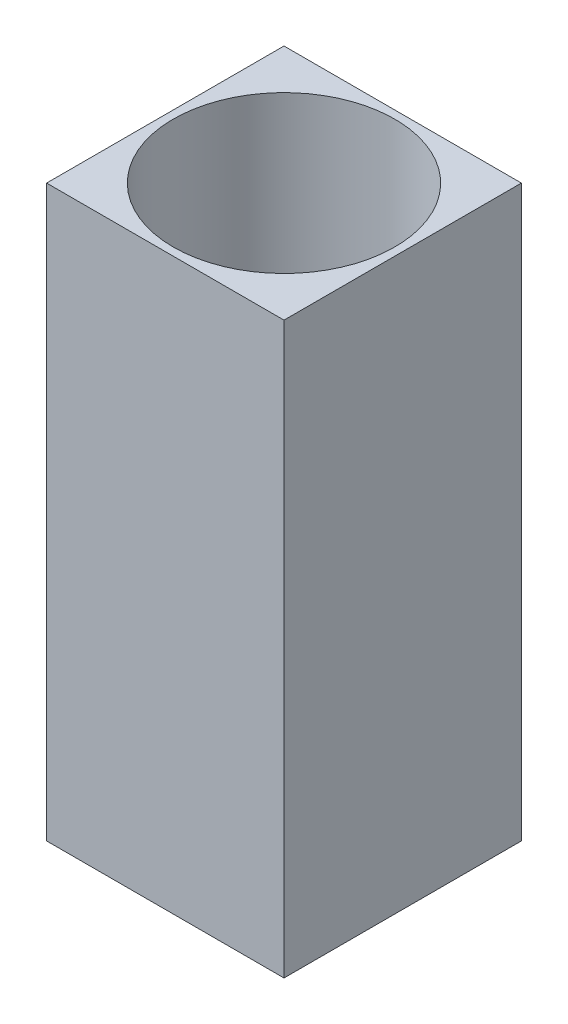
SolidWorks part; units mm, degrees
material "Polyurethane Foam Flexible"
ref_plane "Front Plane" through (0, 0, 0) normal (0, 0, 1) x (1, 0, 0)
ref_plane "Top Plane" through (0, 0, 0) normal (0, 1, 0) x (1, 0, 0)
ref_plane "Right Plane" through (0, 0, 0) normal (1, 0, 0) x (0, 0, -1)
sketch "Sketch1" plane through (0, 0, 0) normal (0, 1, 0) x (1, 0, 0)
  line L1 (0, 0) -> (95.25, 0)
  line L2 (0, 0) -> (0, 95.25)
  line L3 (0, 95.25) -> (95.25, 95.25)
  line L4 (95.25, 0) -> (95.25, 95.25)
  circle A0 centre (47.625, 47.625) radius 44.45
  point P7 (95.25, 47.625)
  point P8 (44.45, 44.45)
  point P9 (47.625, 95.25)
  point P10 (0, 0)
  point P11 (44.45, 44.45)
  dimension "D3" = 88.9
  dimension "D1" = 95.25
  dimension "D2" = 95.25
extrude "Boss-Extrude1" add sketch "Sketch1" along normal blind 215.9
sketch "Sketch2" plane through (0, 0, 0) normal (0, -1, 0) x (1, 0, 0)
  line L4 (0, 0) -> (0, -95.25)
  line L5 (0, -95.25) -> (95.25, -95.25)
  line L6 (95.25, -95.25) -> (95.25, 0)
  line L7 (95.25, 0) -> (0, 0)
  line L8 (0, 0) -> (0, -95.25)
  line L9 (0, -95.25) -> (95.25, -95.25)
  line L10 (95.25, -95.25) -> (95.25, 0)
  line L11 (95.25, 0) -> (0, 0)
  dimension "D1" = 0
extrude "Boss-Extrude2" add sketch "Sketch2" along normal blind 6.35
sketch "Sketch4" plane through (0, 215.9, 0) normal (0, 1, 0) x (1, 0, 0)
  line L4 (0, 95.25) -> (0, 0)
  line L5 (0, 0) -> (95.25, 0)
  line L6 (95.25, 0) -> (95.25, 95.25)
  line L7 (95.25, 95.25) -> (0, 95.25)
  line L8 (0, 95.25) -> (0, 0)
  line L9 (0, 0) -> (95.25, 0)
  line L10 (95.25, 0) -> (95.25, 95.25)
  line L11 (95.25, 95.25) -> (0, 95.25)
  circle A0 centre (47.625, 47.625) radius 44.45 construction
  circle A1 centre (47.625, 47.625) radius 44.45
  dimension "D1" = 0
extrude "Boss-Extrude4" add sketch "Sketch4" along normal blind 6.35
sketch "Sketch5" plane through (0, 222.25, 0) normal (0, 1, 0) x (1, 0, 0)
  circle A0 centre (47.625, 47.625) radius 44.45 construction
  circle A1 centre (47.625, 47.625) radius 44.45
